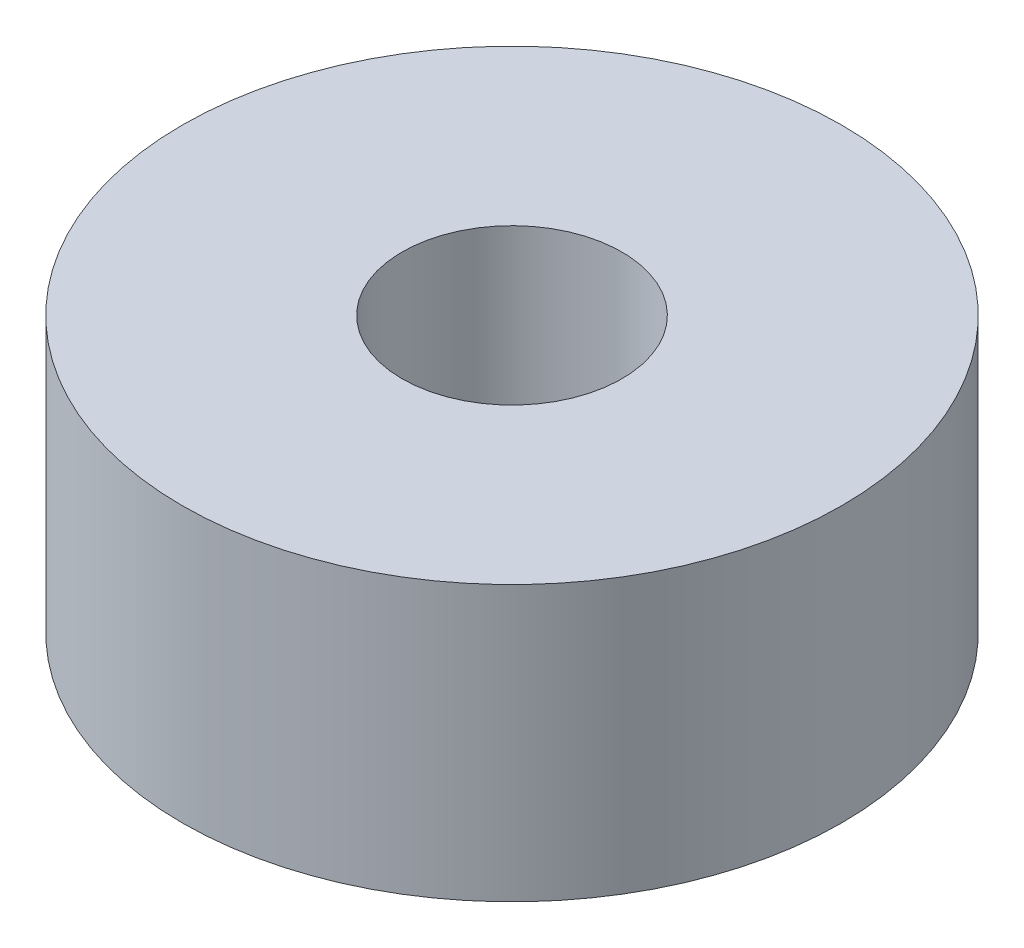
SolidWorks part; units mm, degrees
ref_plane "前视基准面" through (0, 0, 0) normal (0, 0, 1) x (1, 0, 0)
ref_plane "上视基准面" through (0, 0, 0) normal (0, 1, 0) x (1, 0, 0)
ref_plane "右视基准面" through (0, 0, 0) normal (1, 0, 0) x (0, 0, -1)
sketch "草图1" plane through (0, 0, 0) normal (0, 1, 0) x (1, 0, 0)
  circle A0 centre (0, 0) radius 3
  circle A1 centre (0, 0) radius 1
  dimension "D1" = 2
  dimension "D2" = 6
extrude "凸台-拉伸1" add sketch "草图1" along normal blind 2.5
